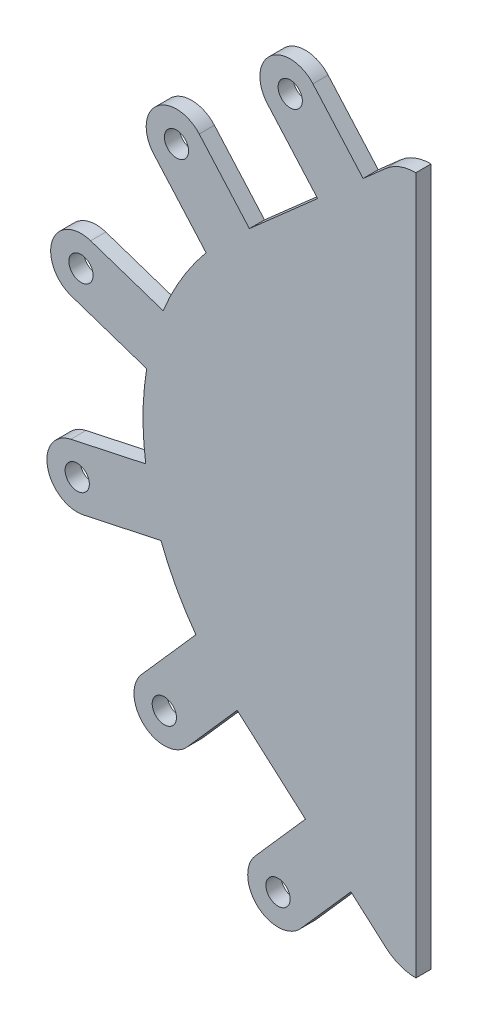
SolidWorks part; units mm, degrees
ref_plane "Спереди" through (0, 0, 0) normal (0, 0, 1) x (1, 0, 0)
ref_plane "Сверху" through (0, 0, 0) normal (0, 1, 0) x (1, 0, 0)
ref_plane "Справа" through (0, 0, 0) normal (1, 0, 0) x (0, 0, -1)
sketch "Эскиз1" plane through (0, 0, 0) normal (0, 0, 1) x (1, 0, 0)
  line L0 (0, 16.3054) -> (0, -20.2512) construction
  line L1 (0, 11.5) -> (0, -11.5)
  line L2 (-5.9529, -6.75) -> (-0.9922, -11.125)
  line L4 (-0.9922, 11.125) -> (-5.9529, 6.75)
  arc A1 (0, 11.5) -> (-0.9922, 11.125) centre (0, 10) ccw
  arc A2 (-5.9529, 6.75) -> (-5.9529, -6.75) centre (0, 0) ccw
  arc A3 (-0.9922, -11.125) -> (0, -11.5) centre (0, -10) ccw
  dimension "D2" = 3
extrude "Вытянуть1" add sketch "Эскиз1" along normal blind 0.5
sketch "Эскиз2" plane through (0, 0, 0.5) normal (0, 0, 1) x (1, 0, 0)
  line L0 (-3.3958, 12.3386) -> (-1.7422, 10.4636)
  line L1 (-0.9922, 11.125) -> (-5.9529, 6.75) construction
  line L2 (-4.8958, 11.0157) -> (-3.2422, 9.1407)
  line L3 (-1.7422, 10.4636) -> (-3.2422, 9.1407)
  circle A0 centre (-4.1458, 11.6771) radius 0.4
  arc A1 (-3.3958, 12.3386) -> (-4.8958, 11.0157) centre (-4.1458, 11.6771) ccw
  arc A2 (0, 11.5) -> (-0.9922, 11.125) centre (0, 10) ccw construction
  dimension "D1" = 0.8
  dimension "D2" = 2
  dimension "D3" = 2.5
  dimension "D4" = 1
extrude "Вытянуть3" add sketch "Эскиз2" against normal blind 0.5
sketch "Эскиз3" plane through (0, 0, 0) normal (0, 0, -1) x (-1, 0, 0)
  line L0 (3.2422, 9.1407) -> (5.9529, 6.75) construction
  line L1 (7.1458, 9.0314) -> (5.4922, 7.1564)
  line L2 (8.6458, 7.7085) -> (6.5597, 5.3431)
  line L3 (2.144, -10.1092) -> (5.4922, 7.1564)
  line L4 (5.9529, -6.75) -> (0.9922, -11.125) construction
  line L5 (10.7275, 4.1914) -> (8.0346, 3.2874)
  line L6 (11.364, 2.2953) -> (8.6881, 1.3971)
  line L7 (11.3796, -1.8022) -> (8.1498, -1.1083)
  line L8 (10.9595, -3.7576) -> (7.51, -3.0165)
  line L9 (5.894, -6.802) -> (7.5476, -8.677)
  line L10 (7.0618, -5.1024) -> (9.0476, -7.3541)
  line L11 (3.644, -8.7863) -> (5.2976, -10.6613)
  line L12 (2.144, -10.1092) -> (3.7976, -11.9842)
  line L13 (3.644, -8.7863) -> (5.894, -6.802)
  line L14 (7.0618, -5.1024) -> (7.51, -3.0165)
  line L15 (8.1498, -1.1083) -> (8.6881, 1.3971)
  line L16 (8.0346, 3.2874) -> (6.5597, 5.3431)
  arc A0 (8.6458, 7.7085) -> (7.1458, 9.0314) centre (7.8958, 8.3699) ccw
  arc A1 (11.364, 2.2953) -> (10.7275, 4.1914) centre (11.0457, 3.2434) ccw
  arc A2 (10.9595, -3.7576) -> (11.3796, -1.8022) centre (11.1696, -2.7799) ccw
  arc A3 (7.5476, -8.677) -> (9.0476, -7.3541) centre (8.2976, -8.0155) ccw
  arc A4 (3.7976, -11.9842) -> (5.2976, -10.6613) centre (4.5476, -11.3227) ccw
  circle A5 centre (7.8958, 8.3699) radius 0.4
  circle A7 centre (11.0457, 3.2434) radius 0.4
  circle A8 centre (11.1696, -2.7799) radius 0.4
  circle A9 centre (8.2976, -8.0155) radius 0.4
  circle A10 centre (4.5476, -11.3227) radius 0.4
  circle A11 centre (4.1458, 11.6771) radius 0.4 construction
extrude "Вытянуть12" add sketch "Эскиз3" against normal blind 0.5
